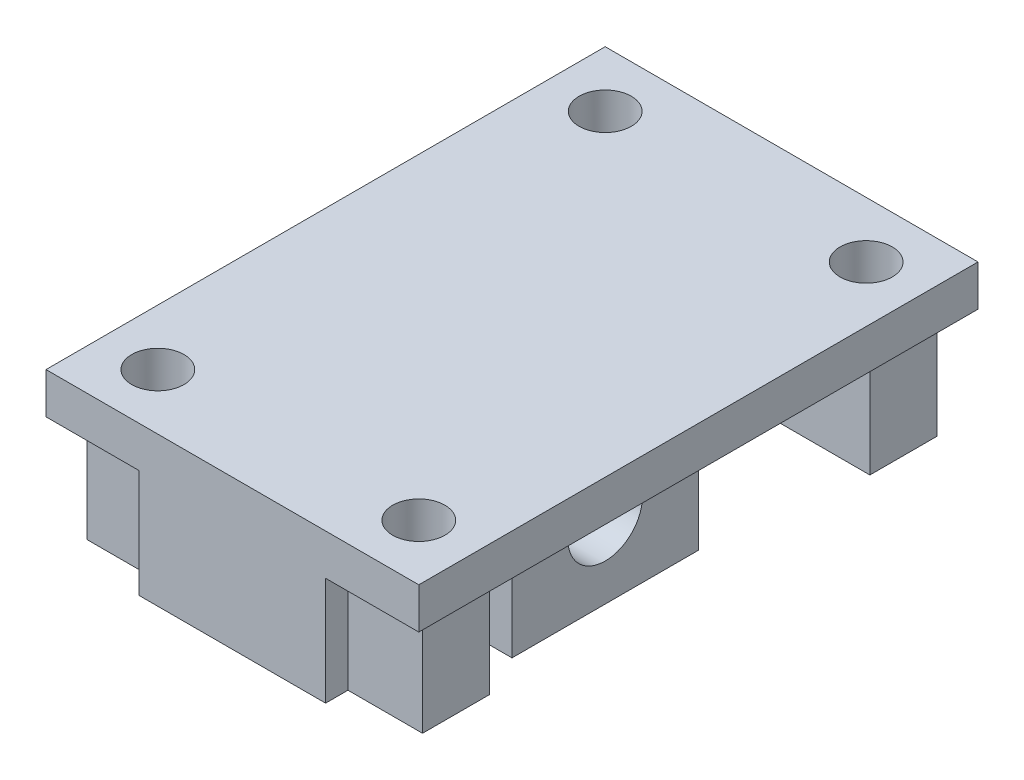
SolidWorks part; units mm, degrees
ref_plane "정면" through (0, 0, 0) normal (0, 0, 1) x (1, 0, 0)
ref_plane "윗면" through (0, 0, 0) normal (0, 1, 0) x (1, 0, 0)
ref_plane "우측면" through (0, 0, 0) normal (1, 0, 0) x (0, 0, -1)
sketch "스케치1" plane through (0, 0, 0) normal (1, 0, 0) x (0, 0, -1)
  line L0 (0, 0) -> (0, 6.8968) construction
  line L1 (15, 6.8968) -> (-15, 6.8968)
  line L2 (-15, 6.8968) -> (-15, -1.1032)
  line L3 (-15, -1.1032) -> (-10.2, -1.1032)
  line L4 (-10.2, -1.1032) -> (-10.2, 4.7)
  line L5 (-10.2, 4.7) -> (-5, 4.7)
  line L6 (-5, 4.7) -> (-5, -4)
  line L7 (-5, -4) -> (5, -4)
  line L8 (5, 4.7) -> (5, -4)
  line L9 (10.2, 4.7) -> (5, 4.7)
  line L10 (10.2, -1.1032) -> (10.2, 4.7)
  line L11 (15, -1.1032) -> (10.2, -1.1032)
  line L12 (15, 6.8968) -> (15, -1.1032)
  circle A0 centre (0, 0) radius 2
  point P12 (0, -4)
  dimension "D1" = 4
  dimension "D2" = 10
  dimension "D3" = 5.2
  dimension "D4" = 4
  dimension "D5" = 4.7
  dimension "D6" = 30
  dimension "D7" = 8
extrude "보스-돌출1" add sketch "스케치1" along normal mid plane 10
sketch "스케치3" plane through (0, 0, 0) normal (1, 0, 0) x (0, 0, -1)
  line L0 (15, -1.1032) -> (15, 6.8968) construction
  line L1 (-15, 6.8968) -> (15, 6.8968)
  line L2 (-15, 6.8968) -> (-15, 4.7)
  line L3 (-15, 4.7) -> (15, 4.7)
  line L4 (15, 6.8968) -> (15, 4.7)
  line L5 (-10.2, 4.7) -> (-5, 4.7) construction
extrude "보스-돌출2" add sketch "스케치3" along normal mid plane 20
sketch "스케치4" plane through (0, 0, 0) normal (0, 1, 0) x (1, 0, 0)
  line L0 (0, 0) -> (-13.0605, 0) construction
  line L1 (0, 0) -> (0, 18.7428) construction
  circle A0 centre (-7, -12) radius 1.4
  circle A1 centre (7, -12) radius 1.4
  circle A2 centre (7, 12) radius 1.4
  circle A3 centre (-7, 12) radius 1.4
  dimension "D1" = 2.8
  dimension "D2" = 12
  dimension "D3" = 7
extrude "컷-돌출2" cut sketch "스케치4" along normal blind 20
sketch "스케치5" plane through (0, 4.7, 0) normal (0, -1, 0) x (1, 0, 0)
  line L1 (-9, -13.8) -> (-5, -13.8)
  line L2 (-9, -13.8) -> (-9, -10.2)
  line L3 (-9, -10.2) -> (-5, -10.2)
  line L4 (-5, -13.8) -> (-5, -10.2)
  line L5 (-9, -13.8) -> (-5, -10.2) construction
  line L6 (-9, -10.2) -> (-5, -13.8) construction
  line L7 (9, -13.8) -> (5, -13.8)
  line L8 (9, -13.8) -> (9, -10.2)
  line L9 (9, -10.2) -> (5, -10.2)
  line L10 (5, -13.8) -> (5, -10.2)
  line L11 (9, -13.8) -> (5, -10.2) construction
  line L12 (9, -10.2) -> (5, -13.8) construction
  line L13 (9, 13.8) -> (5, 13.8)
  line L14 (9, 13.8) -> (9, 10.2)
  line L15 (9, 10.2) -> (5, 10.2)
  line L16 (5, 13.8) -> (5, 10.2)
  line L17 (9, 13.8) -> (5, 10.2) construction
  line L18 (9, 10.2) -> (5, 13.8) construction
  line L19 (-9, 13.8) -> (-5, 13.8)
  line L20 (-9, 13.8) -> (-9, 10.2)
  line L21 (-9, 10.2) -> (-5, 10.2)
  line L22 (-5, 13.8) -> (-5, 10.2)
  line L23 (-9, 13.8) -> (-5, 10.2) construction
  line L24 (-9, 10.2) -> (-5, 13.8) construction
  circle A0 centre (-7, 12) radius 1.4
  circle A1 centre (7, 12) radius 1.4
  circle A2 centre (-7, -12) radius 1.4243
  circle A3 centre (7, -12) radius 1.4
  point P0 (-7, -12)
  point P7 (7, -12)
  point P14 (7, 12)
  point P21 (-7, 12)
extrude "보스-돌출3" add sketch "스케치5" along normal up to surface (5.8032 mm away) up to face at (0, -1.1032, 12.6)
sketch "스케치6" plane through (-5, 0, 0) normal (-1, 0, 0) x (0, 0, 1)
  line L1 (-2.7775, -2.4832) -> (2.7775, -2.4832)
  line L2 (-2.7775, -2.4832) -> (-2.7775, 2.4832)
  line L3 (-2.7775, 2.4832) -> (2.7775, 2.4832)
  line L4 (2.7775, -2.4832) -> (2.7775, 2.4832)
  line L5 (-2.7775, -2.4832) -> (2.7775, 2.4832) construction
  line L6 (-2.7775, 2.4832) -> (2.7775, -2.4832) construction
  point P0 (0, 0)
extrude "보스-돌출4" add sketch "스케치6" against normal blind 7
sketch "스케치8" plane through (-5, 0, 0) normal (-1, 0, 0) x (0, 0, 1)
  circle A0 centre (0, 0) radius 2.9
  dimension "D1" = 5.8
extrude "컷-돌출3" cut sketch "스케치8" against normal blind 5
sketch "스케치9" plane through (0, 0, 0) normal (-1, 0, 0) x (0, 0, 1)
  circle A0 centre (0, 0) radius 2.2
  dimension "D1" = 4.4
extrude "보스-돌출5" add sketch "스케치9" along normal blind 5
fillet "필렛1" radius 1 1 edges at (-5, 0, 2.2)
